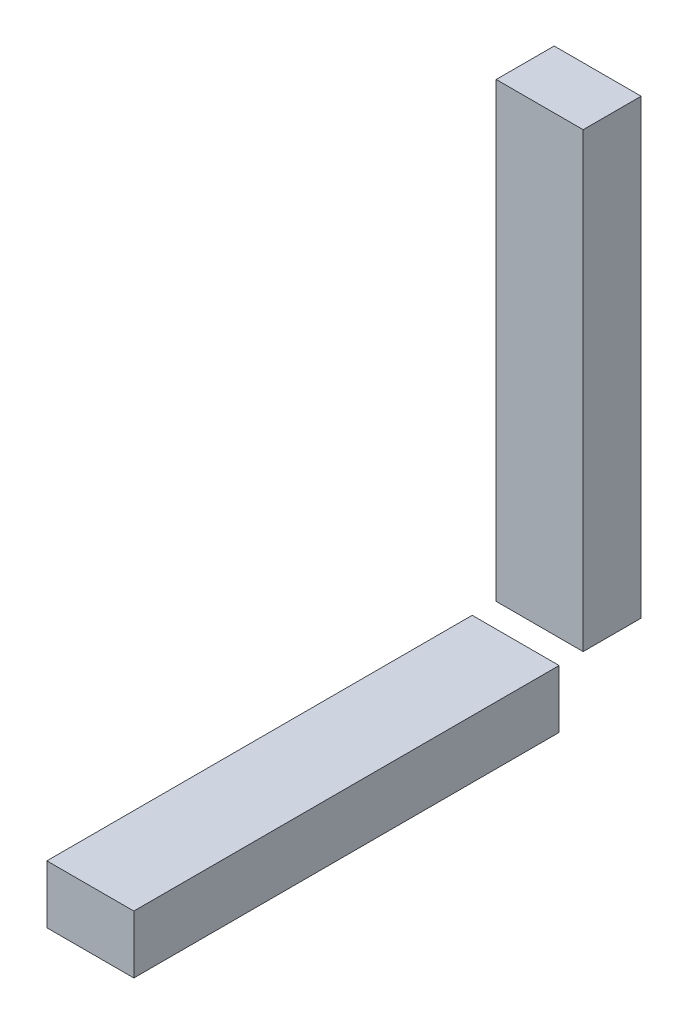
SolidWorks part; units mm, degrees
ref_plane "Front Plane" through (0, 0, 0) normal (0, 0, 1) x (1, 0, 0)
ref_plane "Top Plane" through (0, 0, 0) normal (0, 1, 0) x (1, 0, 0)
ref_plane "Right Plane" through (0, 0, 0) normal (1, 0, 0) x (0, 0, -1)
sketch "Sketch11" plane through (0, 0, 0) normal (0, 0, 1) x (1, 0, 0)
  line L1 (15, -46.3367) -> (-15, -46.3367)
  line L2 (15, -46.3367) -> (15, -202.265)
  line L3 (15, -202.265) -> (-15, -202.265)
  line L4 (-15, -46.3367) -> (-15, -202.265)
  point P9 (0, -46.3367)
  point P11 (0, 0)
  dimension "D2" = 30
extrude "Boss-Extrude2" add sketch "Sketch11" against normal blind 20
sketch "Sketch16" plane through (0, 0, 0) normal (1, 0, 0) x (0, 0, -1)
  line L2 (-8.2843, -222.265) -> (-155, -222.265)
  line L3 (-155, -222.265) -> (-155, -202.265)
  line L6 (-155, -202.265) -> (-8.2843, -202.265)
  line L9 (20, -202.265) -> (0, -202.265) construction
  line L11 (-8.2843, -202.265) -> (-8.2843, -222.265)
  dimension "D2" = 20
extrude "Boss-Extrude3" add sketch "Sketch16" along normal mid plane 30
fillet "Fillet2" [suppressed] radius 1.5
ref_plane "Plane2" through (0, -222.265, 0) normal (0, -1, 0) x (-1, 0, 0)
sketch "Sketch46" plane through (0, 0, -20) normal (0, 0, -1) x (-1, 0, 0)
  line L0 (-10, -45.2873) -> (-10, -47.2873)
  line L1 (-10, -45.2873) -> (-5, -45.2873) construction
  line L2 (-36.898, -45.2873) -> (36.898, -45.2873) construction
  line L3 (-10, -47.2873) -> (-2, -47.2873)
  line L4 (-2, -47.2873) -> (-2, -46.2873)
  line L5 (-2, -46.2873) -> (-5, -46.2873)
  line L6 (-5, -46.2873) -> (-5, -45.2873)
  line L7 (-10, -45.2873) -> (-2, -45.2873) construction
  line L8 (-5, -45.2873) -> (-10, -45.2873)
  line L9 (0, 96.25) -> (0, -96.25) construction
  line L10 (5, -46.2873) -> (5, -45.2873)
  line L11 (2, -46.2873) -> (5, -46.2873)
  line L12 (2, -47.2873) -> (2, -46.2873)
  line L13 (10, -47.2873) -> (2, -47.2873)
  line L14 (10, -45.2873) -> (10, -47.2873)
  line L15 (5, -45.2873) -> (10, -45.2873)
  dimension "D1" = 2
  dimension "D2" = 1
extrude "Cut-Extrude21" [suppressed] cut sketch "Sketch46" against normal blind 18
